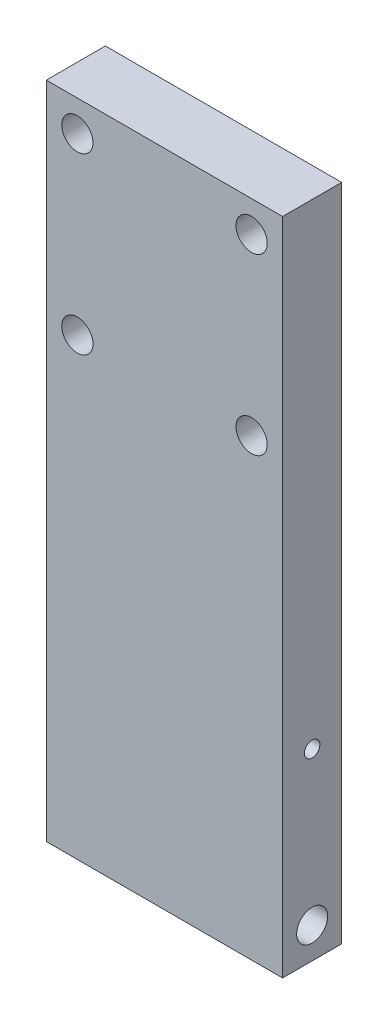
SolidWorks part; units mm, degrees
material "6061-O (SS)"
ref_plane "Alzado" through (0, 0, 0) normal (0, 0, 1) x (1, 0, 0)
ref_plane "Planta" through (0, 0, 0) normal (0, 1, 0) x (1, 0, 0)
ref_plane "Vista lateral" through (0, 0, 0) normal (1, 0, 0) x (0, 0, -1)
sketch "Croquis1" plane through (0, 0, 0) normal (0, 0, 1) x (1, 0, 0)
  line L1 (38.1, 106.35) -> (-38.1, 106.35)
  line L2 (38.1, 106.35) -> (38.1, -106.35)
  line L3 (38.1, -106.35) -> (-38.1, -106.35)
  line L4 (-38.1, 106.35) -> (-38.1, -106.35)
  line L5 (38.1, 106.35) -> (-38.1, -106.35) construction
  line L6 (38.1, -106.35) -> (-38.1, 106.35) construction
  point P0 (0, 0)
  dimension "D1" = 212.7
  dimension "D2" = 76.2
extrude "Saliente-Extruir1" add sketch "Croquis1" along normal mid plane 19.05
hole_wizard "Diámetro de taladro Ø10.0 (10)1" positions "Croquis2" profile "Croquis3" hole size "Ø10.0" standard "DIN" end condition through all
sketch "Croquis2" plane through (38.1, 0, 0) normal (1, 0, 0) x (0, 0, -1)
  line L0 (-9.525, -106.35) -> (9.525, -106.35) construction
  point P0 (0, -96.35)
  point P4 (0, -106.35)
  dimension "D1" = 10
sketch "Croquis3" plane through (38.1, -96.35, 0) normal (0, 1, 0) x (0, 0, -1)
  line L0 (0, 0) -> (0, 76.2)
  line L1 (0, 76.2) -> (5, 76.2)
  line L2 (5, 76.2) -> (5, 0)
  line L5 (5, 0) -> (0, 0)
  line L11 (0, -6.35) -> (0, 107.95) construction
  dimension "Diámetro de taladro hasta el siguiente" = 10
  dimension "Profundidad de taladro hasta el siguiente" = 76.2
hole_wizard "Taladro roscado M61" positions "Croquis4" profile "Croquis5" tap size "M6" standard "DIN"
sketch "Croquis4" plane through (38.1, 0, 0) normal (1, 0, 0) x (0, 0, -1)
  point P0 (0, -47.15)
sketch "Croquis5" plane through (38.1, -47.15, 0) normal (0, 1, 0) x (0, 0, -1)
  line L0 (0, 0) -> (0, 11.5022)
  line L1 (0, 11.5022) -> (2.5, 10)
  line L2 (2.5, 10) -> (2.5, 0)
  line L5 (2.5, 0) -> (0, 0)
  line L10 (0, 11.5022) -> (-2.5, 10) construction
  line L11 (0, -6.35) -> (0, 107.95) construction
  dimension "Diámetro de perforador para roscar" = 5
  dimension "Profundidad de perforador para roscar" = 10
  dimension "Ángulo de perforador" = 118
cosmetic thread "Rosca de taladro1"
hole_wizard "Taladro de margen para 3/81" positions "Croquis8" profile "Croquis9" hole size "3/8" standard "Ansi Inch" end condition through all
sketch "Croquis8" plane through (0, 0, -9.525) normal (0, 0, -1) x (-1, 0, 0)
  line L0 (0, 0) -> (0, 50000) construction
  line L1 (-38.1, 106.35) -> (38.1, 106.35) construction
  line L2 (-38.1, 106.35) -> (-38.1, -106.35) construction
  point P0 (-28.1, 96.35)
  point P2 (-28.1, 40.15)
  point P8 (28.1, 40.15)
  point P9 (28.1, 96.35)
  dimension "D1" = 10
  dimension "D2" = 10
  dimension "D3" = 56.2
sketch "Croquis9" plane through (28.1, 96.35, -9.525) normal (1, 0, 0) x (0, 1, 0)
  line L0 (0, 0) -> (0, 19.05)
  line L1 (0, 19.05) -> (5.0419, 19.05)
  line L2 (5.0419, 19.05) -> (5.0419, 0)
  line L5 (5.0419, 0) -> (0, 0)
  line L11 (0, -6.35) -> (0, 107.95) construction
  dimension "Diámetro de taladro hasta el siguiente" = 10.0838
  dimension "Profundidad de taladro hasta el siguiente" = 19.05
equation "\"D2@Croquis8\"=\"D1@Croquis8\""
